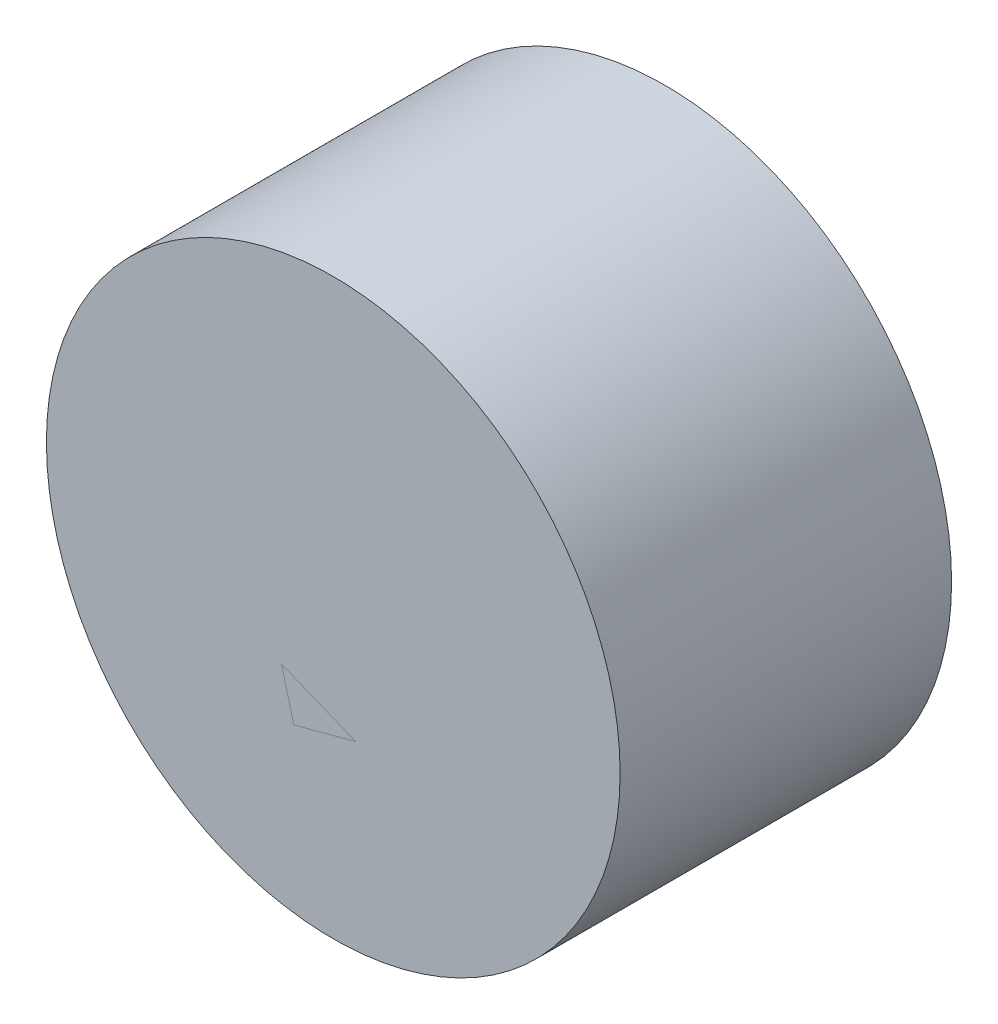
SolidWorks part; units mm, degrees
ref_plane "Front Plane" through (0, 0, 0) normal (0, 0, 1) x (1, 0, 0)
ref_plane "Top Plane" through (0, 0, 0) normal (0, 1, 0) x (1, 0, 0)
ref_plane "Right Plane" through (0, 0, 0) normal (1, 0, 0) x (0, 0, -1)
sketch "Sketch1" plane through (0, 0, 0) normal (0, 0, 1) x (1, 0, 0)
  circle A0 centre (-65.394, -33.4556) radius 11.25
  dimension "D1" = 22.5
extrude "Boss-Extrude1" add sketch "Sketch1" along normal blind 13
shell "Shell1" thickness 3
sketch "Sketch2" plane through (0, 0, 0) normal (0, 0, 1) x (1, 0, 0)
  circle A0 centre (-65.394, -33.4556) radius 5
  point P3 (0, 0)
  point P5 (0, 0)
  dimension "D1" = 10
  dimension "D2" = 33.4556
  dimension "D3" = 65.394
extrude "Boss-Extrude2" add sketch "Sketch2" along normal blind 13 separate body
shell "Shell2" thickness 1
sketch "Sketch4" plane through (0, 0, 13) normal (0, 0, 1) x (1, 0, 0)
  line L0 (-67.8886, -34.8373) -> (-62.6437, -33.2502)
  line L1 (-62.6437, -33.2502) -> (-62.9738, -32.0963)
  line L2 (-62.9738, -32.0963) -> (-68.3568, -33.7253)
  line L4 (-67.8886, -34.8373) -> (-68.3568, -33.7253)
  circle A0 centre (-65.394, -33.4556) radius 11.25 construction
  point P4 (0, 0)
  point P7 (0, 0)
  point P8 (0, 0)
  point P10 (0, 0)
  dimension "D8" = 0.6
  dimension "D1" = 5.6241
  dimension "D2" = 1.2001
  dimension "D3" = 5.4798
  dimension "D4" = 1.2066
  dimension "D5" = 12.4809
  dimension "D6" = 69.3722
  dimension "D7" = 0.6
extrude "Boss-Extrude3" add sketch "Sketch4" against normal blind 8.5 separate body
